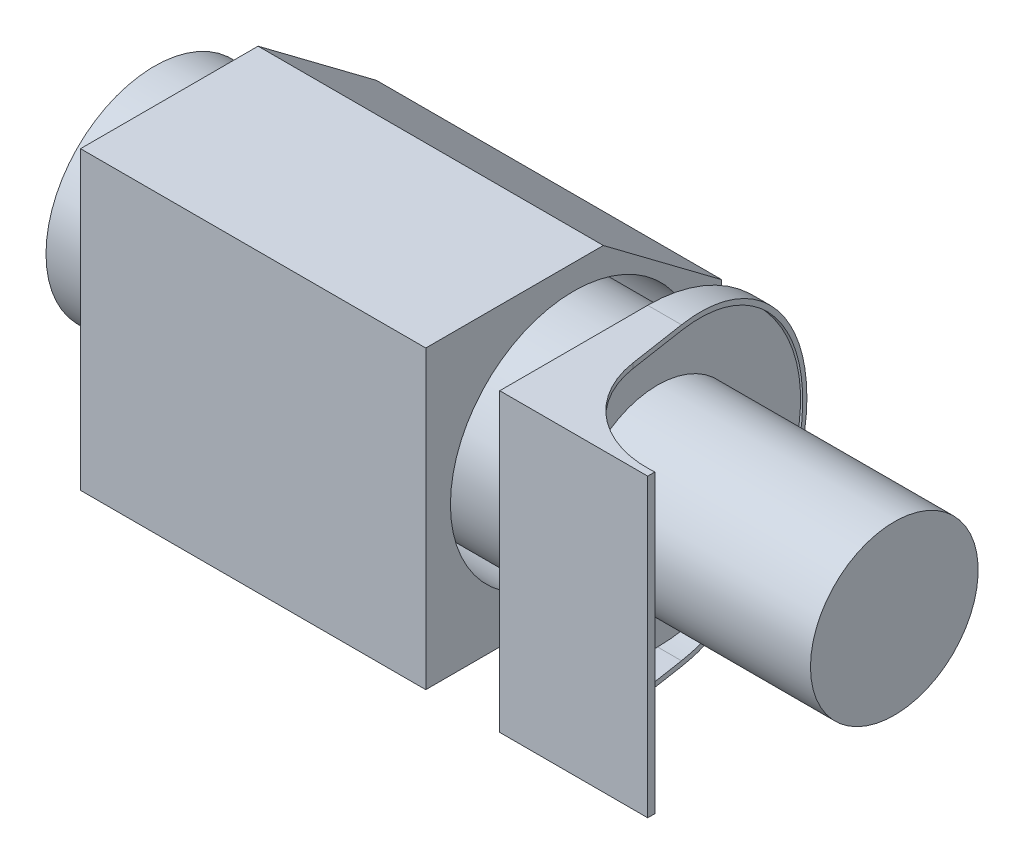
SolidWorks part; units mm, degrees
ref_plane "Front Plane" through (0, 0, 0) normal (0, 0, 1) x (1, 0, 0)
ref_plane "Top Plane" through (0, 0, 0) normal (0, 1, 0) x (1, 0, 0)
ref_plane "Right Plane" through (0, 0, 0) normal (1, 0, 0) x (0, 0, -1)
sketch "Sketch1" plane through (0, 0, 0) normal (0, 1, 0) x (1, 0, 0)
  line L1 (0, 0) -> (300, 0)
  line L2 (0, 0) -> (0, 600)
  line L3 (0, 600) -> (300, 600)
  line L4 (300, 0) -> (300, 600)
  dimension "D1" = 300
  dimension "D2" = 600
extrude "Boss-Extrude1" add sketch "Sketch1" along normal blind 600 contours L3 L4 L1 L2
sketch "Sketch3" plane through (0, 0, 0) normal (-1, 0, 0) x (0, 0, 1)
  line L1 (0, 600) -> (-300, 600)
  line L2 (0, 600) -> (0, 0)
  line L3 (0, 0) -> (-300, 0)
  arc A0 (-300, 600) -> (-300, 0) centre (-300, 300) ccw
extrude "Cut-Extrude1" cut sketch "Sketch3" against normal through all flip side to cut
sketch "Sketch4" plane through (0, 0, 0) normal (0, -1, 0) x (1, 0, 0)
  line L0 (300, 0) -> (300, -300) construction
  line L1 (97.9148, -107.0961) -> (22.7827, -600)
  line L2 (0, -600) -> (300, -600) construction
  line L3 (22.7827, -600) -> (300, -600)
  line L4 (300, -600) -> (300, -300) construction
  line L5 (300, -600) -> (300, -14.5116)
  spline S0 degree 2 poles (300, -14.5116) (162.2644, -6.0547) (97.9148, -107.0961) knots 0 0 0 1 1 1
  point P2 (0, 0)
  point P12 (0, 0)
  point P13 (98.1597, -107.0961)
  point P14 (0, 0)
extrude "Cut-Extrude2" cut sketch "Sketch4" against normal through all
fillet "Fillet1" radius 200 1 edges at (97.9148, 300, -107.0961)
sketch "Sketch5" plane through (0, 0, 0) normal (-1, 0, 0) x (0, 0, 1)
  circle A0 centre (-300, 300) radius 220
  dimension "D1" = 440
extrude "Boss-Extrude2" add sketch "Sketch5" along normal blind 1000
sketch "Sketch6" plane through (0, 0, 0) normal (-1, 0, 0) x (0, 0, 1)
  circle A0 centre (-300, 300) radius 170
extrude "Boss-Extrude3" add sketch "Sketch6" against normal blind 500
sketch "Sketch7" plane through (300, 0, 0) normal (1, 0, 0) x (0, 0, -1)
  line L0 (14.5116, 600) -> (14.5116, 0) construction
  line L3 (300, 590) -> (14.5116, 590)
  line L4 (14.5116, 300) -> (14.5116, 590)
  line L8 (300, 10) -> (14.5116, 10)
  line L9 (14.5116, 300) -> (14.5116, 10)
  circle A0 centre (300, 300) radius 170
  arc A2 (300, 10) -> (300, 590) centre (300, 300) ccw
extrude "Cut-Extrude3" cut sketch "Sketch7" against normal blind 280
ref_plane "Plane1" through (-150, 0, 0) normal (-1, 0, 0) x (0, 0, 1)
sketch "Sketch8" plane through (-150, 0, 0) normal (-1, 0, 0) x (0, 0, 1)
  line L0 (-360, 600) -> (-600, 420)
  line L1 (0, 600) -> (-360, 600)
  line L2 (0, 600) -> (0, 0)
  line L3 (0, 0) -> (-360, 0)
  line L4 (-600, 420) -> (-600, 180)
  line L5 (-360, 0) -> (-600, 180)
  circle A0 centre (-300, 300) radius 250
  dimension "D2" = 240
  dimension "D3" = 180
  dimension "D4" = 180
  dimension "D5" = 240
extrude "Boss-Extrude4" add sketch "Sketch8" along normal blind 700 separate body
